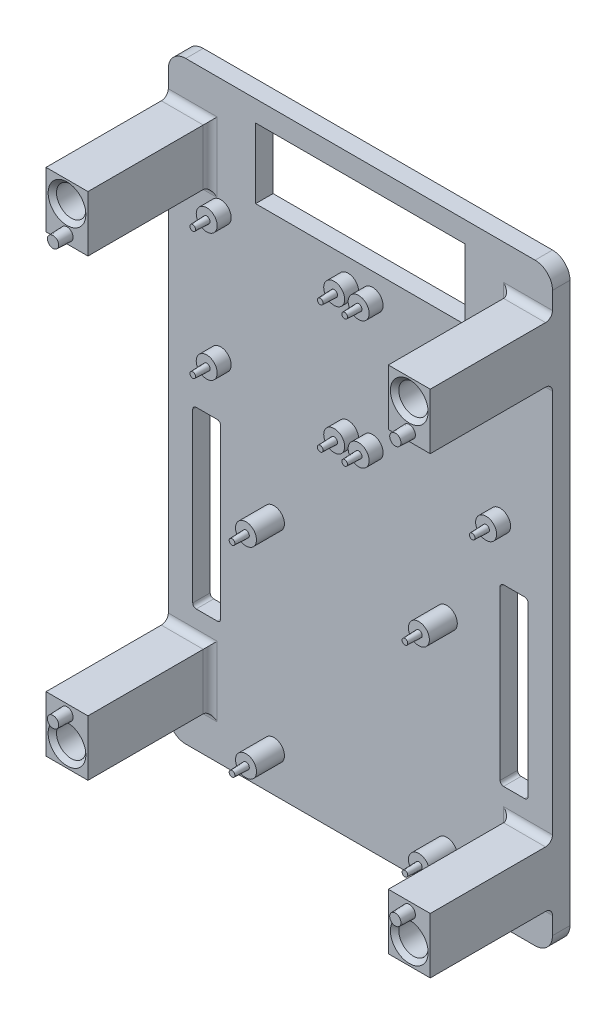
SolidWorks part; units mm, degrees
ref_plane "Ebene vorne" through (0, 0, 0) normal (0, 0, 1) x (1, 0, 0)
ref_plane "Ebene oben" through (0, 0, 0) normal (0, 1, 0) x (1, 0, 0)
ref_plane "Ebene rechts" through (0, 0, 0) normal (1, 0, 0) x (0, 0, -1)
sketch "Skizze1" plane through (0, 0, 0) normal (0, 0, 1) x (1, 0, 0)
  line L1 (-55, -85) -> (55, -85)
  line L2 (-55, -85) -> (-55, 85)
  line L3 (-55, 85) -> (55, 85)
  line L4 (55, -85) -> (55, 85)
  line L5 (-55, -85) -> (55, 85) construction
  line L6 (-55, 85) -> (55, -85) construction
  point P0 (0, 0)
  dimension "D1" = 110
  dimension "D2" = 170
extrude "Aufsatz-Linear austragen1" add sketch "Skizze1" along normal blind 5
fillet "Verrundung1" radius 5 4 edges at (-55, -85, 2.5) (55, -85, 2.5) (55, 85, 2.5) (-55, 85, 2.5)
sketch "Skizze7" plane through (0, 0, 5) normal (0, 0, 1) x (1, 0, 0)
  line L0 (-55, 80) -> (-55, -80) construction
  line L1 (-55, 73) -> (-43, 73)
  line L2 (-55, 73) -> (-55, 57)
  line L3 (-55, 57) -> (-43, 57)
  line L4 (-43, 73) -> (-43, 57)
  line L5 (50, 85) -> (-50, 85) construction
  line L18 (0, 85) -> (0, -85) construction
  line L19 (-50, -85) -> (50, -85) construction
  line L20 (-55, 0) -> (55, 0) construction
  line L21 (55, -80) -> (55, 80) construction
  line L22 (43, 73) -> (43, 57)
  line L23 (55, 57) -> (43, 57)
  line L24 (55, 73) -> (55, 57)
  line L25 (55, 73) -> (43, 73)
  line L26 (55, -73) -> (43, -73)
  line L27 (55, -73) -> (55, -57)
  line L28 (55, -57) -> (43, -57)
  line L29 (43, -73) -> (43, -57)
  line L30 (-43, -73) -> (-43, -57)
  line L31 (-55, -57) -> (-43, -57)
  line L32 (-55, -73) -> (-55, -57)
  line L33 (-55, -73) -> (-43, -73)
  dimension "D1" = 12
  dimension "D2" = 16
  dimension "D3" = 12
extrude "Aufsatz-Linear austragen3" add sketch "Skizze7" along normal blind 35
fillet "Verrundung2" radius 2 12 edges at (-49, 73, 5) (-49, 57, 5) (-43, 65, 5) (-49, -57, 5) (-43, -65, 5) (-49, -73, 5) (49, -73, 5) (43, -65, 5) (49, -57, 5) (49, 57, 5) (43, 65, 5) (49, 73, 5)
sketch "Skizze8" plane through (0, 0, 40) normal (0, 0, 1) x (1, 0, 0)
  line L0 (-43, 73) -> (-55, 73) construction
  line L1 (-55, 73) -> (-55, 57) construction
  line L5 (-55, 31.954) -> (-55, -16.1316) construction
  line L8 (-55, 55) -> (-55, -55) construction
  circle A1 centre (-49, 67) radius 4.2
  dimension "D1" = 8.4
  dimension "D2" = 6
  dimension "D3" = 6
extrude "Schnitt-Linear austragen3" cut sketch "Skizze8" against normal through all
pattern_linear "Lineares Muster1" count 2 spacing 134 along (0, -1, 0) count 2 spacing 98 along (1, 0, 0) of "Schnitt-Linear austragen3"
sketch "Skizze9" plane through (0, 0, 5) normal (0, 0, 1) x (1, 0, 0)
  line L0 (0, 85) -> (0, -85) construction
  line L1 (-28, -77) -> (28, -77) construction
  line L2 (-28, -77) -> (-28, 12) construction
  line L3 (-28, 12) -> (28, 12) construction
  line L4 (28, -77) -> (28, 12) construction
  line L5 (-28, -77) -> (28, 12) construction
  line L6 (-28, 12) -> (28, -77) construction
  line L11 (50, 85) -> (-50, 85) construction
  line L12 (-50, -85) -> (50, -85) construction
  line L13 (-55, 55) -> (-55, -55) construction
  line L14 (-40, 15.5) -> (-3.5, 15.5) construction
  line L15 (-40, 15.5) -> (-40, 52) construction
  line L16 (-40, 52) -> (-3.5, 52) construction
  line L17 (-3.5, 15.5) -> (-3.5, 52) construction
  line L18 (-40, 15.5) -> (-3.5, 52) construction
  line L19 (-40, 52) -> (-3.5, 15.5) construction
  line L20 (40, 52) -> (3.5, 15.5) construction
  line L26 (40, 15.5) -> (3.5, 52) construction
  line L35 (3.5, 15.5) -> (3.5, 52) construction
  line L36 (40, 52) -> (3.5, 52) construction
  line L37 (40, 15.5) -> (40, 52) construction
  line L38 (40, 15.5) -> (3.5, 15.5) construction
  circle A0 centre (24.75, -73.75) radius 3
  circle A1 centre (24.75, -16.25) radius 3
  circle A2 centre (-24.75, -16.25) radius 3
  circle A3 centre (-24.75, -73.75) radius 3
  circle A16 centre (-3.5, 52) radius 3
  circle A17 centre (-40, 52) radius 3
  circle A18 centre (-40, 15.5) radius 3
  circle A19 centre (-3.5, 15.5) radius 3
  circle A20 centre (3.5, 15.5) radius 3
  circle A21 centre (40, 15.5) radius 3
  circle A22 centre (40, 52) radius 3
  circle A23 centre (3.5, 52) radius 3
  point P0 (0, 0)
  point P5 (0, -32.5)
  point P21 (-21.75, 33.75)
  point P36 (21.75, 33.75)
  dimension "D3" = 3.25
  dimension "D4" = 6
  dimension "D5" = 57.5
  dimension "D13" = 6
  dimension "D1" = 56
  dimension "D2" = 89
  dimension "D6" = 3.25
  dimension "D7" = 8
  dimension "D8" = 28
  dimension "D9" = 36.5
  dimension "D10" = 36.5
  dimension "D11" = 15
  dimension "D12" = 33
extrude "Aufsatz-Linear austragen4" add sketch "Skizze9" along normal blind 4
sketch "Skizze10" plane through (0, 0, 9) normal (0, 0, 1) x (1, 0, 0)
  line L0 (0, -85) -> (0, 85) construction
  line L1 (-50, -85) -> (50, -85) construction
  line L2 (50, 85) -> (-50, 85) construction
  circle A20 centre (3.5, 15.5) radius 0.95
  circle A21 centre (40, 15.5) radius 0.95
  circle A22 centre (40, 52) radius 0.95
  circle A23 centre (3.5, 52) radius 0.95
  circle A24 centre (-3.5, 52) radius 0.95
  circle A25 centre (-40, 52) radius 0.95
  circle A26 centre (-40, 15.5) radius 0.95
  circle A27 centre (-3.5, 15.5) radius 0.95
  dimension "D2" = 1.9
extrude "Aufsatz-Linear austragen5" add sketch "Skizze10" along normal blind 4 draft 2
chamfer "Fase1" distance 1.2 angle 45 4 edges at (-44.8, 67, 40) (-44.8, -67, 40) (53.2, -67, 40) (53.2, 67, 40)
sketch "Skizze11" plane through (0, 0, 5) normal (0, 0, 1) x (1, 0, 0)
  line L0 (0, 85) -> (0, -85) construction
  line L1 (-30, 59) -> (30, 59)
  line L2 (-30, 59) -> (-30, 79)
  line L3 (-30, 79) -> (30, 79)
  line L4 (30, 59) -> (30, 79)
  line L5 (-30, 59) -> (30, 79) construction
  line L6 (-30, 79) -> (30, 59) construction
  line L7 (50, 85) -> (-50, 85) construction
  line L8 (-50, -85) -> (50, -85) construction
  point P0 (0, 69)
  dimension "D1" = 60
  dimension "D2" = 20
  dimension "D3" = 6
extrude "Schnitt-Linear austragen4" cut sketch "Skizze11" against normal through all
sketch "Skizze12" plane through (0, 0, 40) normal (0, 0, 1) x (1, 0, 0)
  line L0 (-49, 73) -> (-49, 57) construction
  line L1 (-43, 73) -> (-55, 73) construction
  line L2 (-55, 57) -> (-43, 57) construction
  line L3 (-43, 67) -> (-55, 67) construction
  line L4 (-43, 57) -> (-43, 73) construction
  line L5 (-55, 73) -> (-55, 57) construction
  line L6 (0, 85) -> (0, -85) construction
  line L7 (50, 85) -> (-50, 85) construction
  line L8 (-50, -85) -> (50, -85) construction
  line L9 (-55, 0) -> (55, 0) construction
  line L10 (-55, 55) -> (-55, -55) construction
  line L11 (55, -55) -> (55, 55) construction
  circle A0 centre (-49, 59.5) radius 1.75
  circle A1 centre (49, 59.5) radius 1.75
  circle A2 centre (-49, -59.5) radius 1.75
  circle A3 centre (49, -59.5) radius 1.75
  dimension "D1" = 3.5
  dimension "D2" = 7.5
extrude "Aufsatz-Linear austragen6" add sketch "Skizze12" along normal blind 4 draft 2
sketch "Skizze13" plane through (0, 0, 0) normal (0, 0, -1) x (-1, 0, 0)
  line L0 (49, 71.2) -> (49, 62.8) construction
  line L1 (44.8, 67) -> (53.2, 67) construction
  line L2 (0, 85) -> (0, -85) construction
  line L3 (-50, 85) -> (50, 85) construction
  line L4 (50, -85) -> (-50, -85) construction
  line L5 (-55, 0) -> (55, 0) construction
  line L6 (-55, -80) -> (-55, 80) construction
  line L7 (55, 80) -> (55, -80) construction
  circle A0 centre (49, 67) radius 4.2 construction
  circle A1 centre (49, 59.5) radius 2
  circle A2 centre (-49, 59.5) radius 2
  circle A3 centre (-49, -59.5) radius 2
  circle A4 centre (49, -59.5) radius 2
  dimension "D1" = 4
  dimension "D2" = 7.5
extrude "Schnitt-Linear austragen5" cut sketch "Skizze13" against normal blind 4.5
sketch "Skizze15" plane through (0, 0, 5) normal (0, 0, 1) x (1, 0, 0)
  line L0 (55, -55) -> (55, 55) construction
  line L1 (48, -50) -> (40, -50)
  line L2 (48, -50) -> (48, 0)
  line L3 (48, 0) -> (40, 0)
  line L4 (40, -50) -> (40, 0)
  line L5 (-50, -85) -> (50, -85) construction
  line L6 (0, -85) -> (0, 85) construction
  line L7 (50, 85) -> (-50, 85) construction
  line L8 (-48, 0) -> (-40, 0)
  line L9 (-40, -50) -> (-40, 0)
  line L10 (-48, -50) -> (-40, -50)
  line L11 (-48, -50) -> (-48, 0)
  dimension "D1" = 50
  dimension "D2" = 8
  dimension "D3" = 7
  dimension "D4" = 35
extrude "Schnitt-Linear austragen6" cut sketch "Skizze15" against normal through all
fillet "Verrundung3" radius 1 8 edges at (48, 0, 2.5) (40, 0, 2.5) (48, -50, 2.5) (40, -50, 2.5) (-40, -50, 2.5) (-48, -50, 2.5) (-40, 0, 2.5) (-48, 0, 2.5)
sketch "Skizze16" plane through (0, 0, 9) normal (0, 0, 1) x (1, 0, 0)
  circle A0 centre (-24.75, -16.25) radius 3
  circle A1 centre (24.75, -16.25) radius 3
  circle A2 centre (-24.75, -73.75) radius 3
  circle A3 centre (24.75, -73.75) radius 3
extrude "Aufsatz-Linear austragen7" add sketch "Skizze16" along normal blind 4
sketch "Skizze17" plane through (0, 0, 13) normal (0, 0, 1) x (1, 0, 0)
  circle A0 centre (-24.75, -16.25) radius 0.95
  circle A1 centre (24.75, -16.25) radius 0.95
  circle A2 centre (-24.75, -73.75) radius 0.95
  circle A3 centre (24.75, -73.75) radius 0.95
  dimension "D1" = 1.9
extrude "Aufsatz-Linear austragen8" add sketch "Skizze17" along normal blind 4 draft 2
